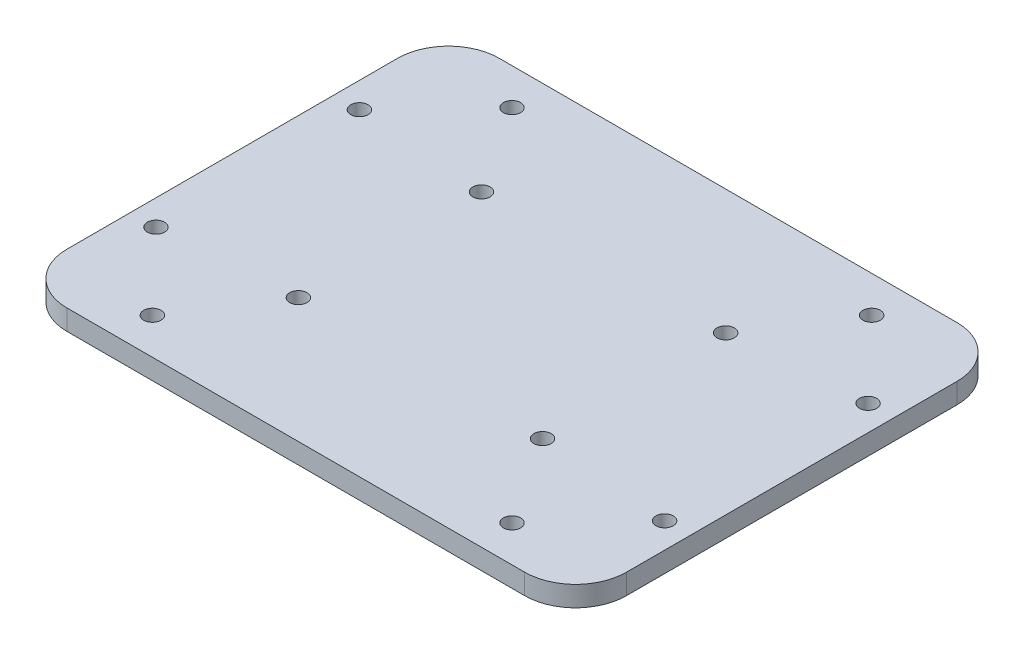
SolidWorks part; units mm, degrees
ref_plane "前视基准面" through (0, 0, 0) normal (0, 0, 1) x (1, 0, 0)
ref_plane "上视基准面" through (0, 0, 0) normal (0, 1, 0) x (1, 0, 0)
ref_plane "右视基准面" through (0, 0, 0) normal (1, 0, 0) x (0, 0, -1)
other "Configuration Table"
sketch "草图1" plane through (0, 0, 0) normal (0, 1, 0) x (1, 0, 0)
  line L1 (-35.355, 35.355) -> (35.355, 35.355) construction
  line L2 (-35.355, 35.355) -> (-35.355, -35.355) construction
  line L3 (-35.355, -35.355) -> (35.355, -35.355) construction
  line L4 (35.355, 35.355) -> (35.355, -35.355) construction
  line L5 (-35.355, 35.355) -> (35.355, -35.355) construction
  line L6 (-35.355, -35.355) -> (35.355, 35.355) construction
  line L7 (-24, 18) -> (24, 18) construction
  line L8 (-24, 18) -> (-24, -18) construction
  line L9 (-24, -18) -> (24, -18) construction
  line L10 (24, 18) -> (24, -18) construction
  line L11 (-24, 18) -> (24, -18) construction
  line L12 (-24, -18) -> (24, 18) construction
  line L13 (-55, 42.5) -> (55, 42.5)
  line L14 (-55, 42.5) -> (-55, -42.5)
  line L15 (-55, -42.5) -> (55, -42.5)
  line L16 (55, 42.5) -> (55, -42.5)
  line L17 (-55, 42.5) -> (55, -42.5) construction
  line L18 (-55, -42.5) -> (55, 42.5) construction
  circle A0 centre (24, 18) radius 1.7
  circle A1 centre (-24, 18) radius 1.7
  circle A2 centre (-24, -18) radius 1.7
  circle A3 centre (24, -18) radius 1.7
  circle A4 centre (-35.355, 35.355) radius 1.7
  circle A5 centre (35.355, 35.355) radius 1.7
  circle A6 centre (35.355, -35.355) radius 1.7
  circle A7 centre (-35.355, -35.355) radius 1.7
  point P0 (0, 0)
  point P6 (0, 0)
  point P19 (0, 0)
  dimension "D3" = 3.4
  dimension "D1" = 70.71
  dimension "D2" = 48
  dimension "D4" = 36
  dimension "D5" = 70.71
  dimension "D6" = 110
  dimension "D7" = 85
extrude "凸台-拉伸1" add sketch "草图1" along normal blind 4
sketch "草图2" plane through (0, 4, 0) normal (0, 1, 0) x (1, 0, 0)
  line L0 (-55, 42.5) -> (-55, -42.5) construction
  line L1 (-50, 20) -> (50, 20) construction
  line L2 (-50, 20) -> (-50, -20) construction
  line L3 (-50, -20) -> (50, -20) construction
  line L4 (50, 20) -> (50, -20) construction
  line L5 (-50, 20) -> (50, -20) construction
  line L6 (-50, -20) -> (50, 20) construction
  circle A0 centre (50, 20) radius 1.7
  circle A1 centre (50, -20) radius 1.7
  circle A2 centre (-50, 20) radius 1.7
  circle A3 centre (-50, -20) radius 1.7
  point P0 (0, 0)
  dimension "D1" = 3.4
  dimension "D2" = 40
  dimension "D3" = 5
extrude "切除-拉伸1" cut sketch "草图2" against normal blind 10
fillet "圆角1" radius 10 4 edges at (55, 2, 42.5) (-55, 2, -42.5) (55, 2, -42.5) (-55, 2, 42.5)
